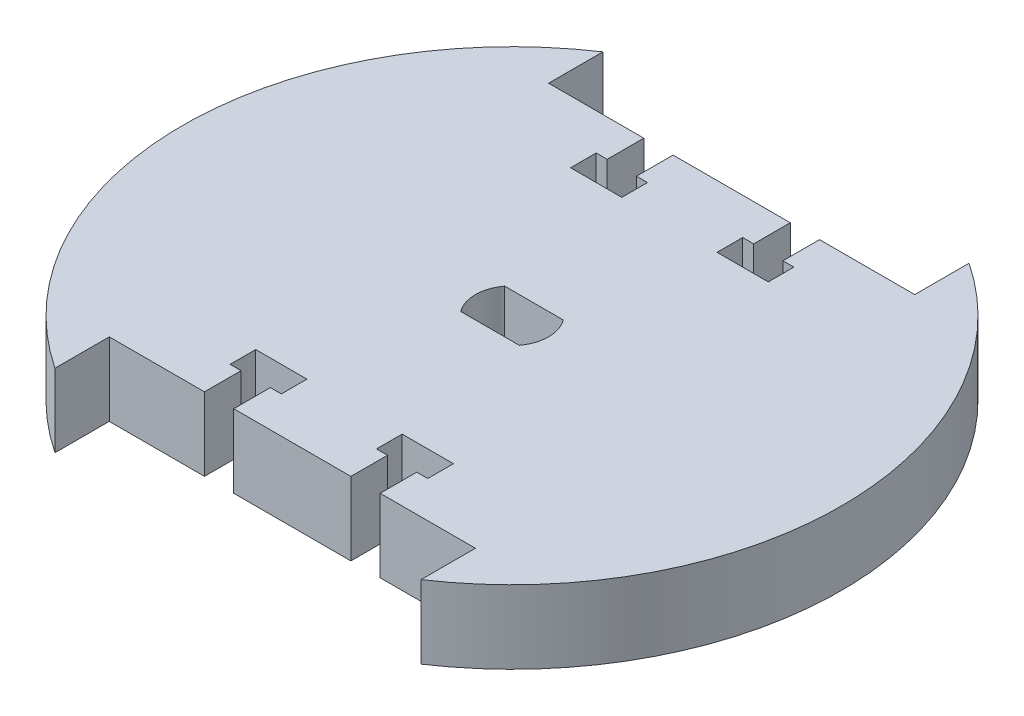
SolidWorks part; units mm, degrees
ref_plane "Piano frontale" through (0, 0, 0) normal (0, 0, 1) x (1, 0, 0)
ref_plane "Piano superiore" through (0, 0, 0) normal (0, 1, 0) x (1, 0, 0)
ref_plane "Piano destro" through (0, 0, 0) normal (1, 0, 0) x (0, 0, -1)
sketch "Schizzo1" plane through (0, 0, 0) normal (0, 1, 0) x (1, 0, 0)
  line L0 (-42.1632, 0) -> (43.9871, 0) construction
  line L1 (0, 30) -> (0, 0) construction
  line L2 (-25, 37.4166) -> (-25, 30)
  line L3 (-25, 30) -> (25, 30)
  line L4 (25, 37.4166) -> (25, 30)
  line L5 (0, 0) -> (0, -30) construction
  line L8 (-25, -37.4166) -> (-25, -30)
  line L9 (-25, -30) -> (25, -30)
  line L10 (25, -37.4166) -> (25, -30)
  arc A0 (-25, 37.4166) -> (-25, -37.4166) centre (0, 0) ccw
  arc A1 (25, -37.4166) -> (25, 37.4166) centre (0, 0) ccw
  point P3 (0, 45)
  point P8 (0, -45)
  dimension "D1" = 90
  dimension "D2" = 60
  dimension "D3" = 50
  dimension "D4" = 50
extrude "Estrusione-Estrusione1" add sketch "Schizzo1" along normal blind 10
sketch "Schizzo3" plane through (0, 10, 0) normal (0, 1, 0) x (1, 0, 0)
  line L0 (4, 3) -> (-4, 3)
  line L1 (-4, -3) -> (4, -3)
  line L2 (4, -3) -> (4, 3)
  line L3 (-4, 3) -> (-4, -3)
  circle A0 centre (0, 0) radius 5
  dimension "D1" = 10
  dimension "D2" = 6
extrude "Taglio-Estrusione2" cut sketch "Schizzo3" against normal through all contours L3 A0 | L0 L3 L1 L2 | L2 A0
sketch "Schizzo5" plane through (0, 10, 0) normal (0, 1, 0) x (1, 0, 0)
  line L1 (0, 0) -> (-13.5, 0)
  line L2 (-13.5, 25) -> (-12, 25)
  line L3 (-13.5, 21.5) -> (-13.5, 25)
  line L4 (-6.5, 25) -> (-6.5, 21.5)
  line L5 (13.5, 25) -> (13.5, 21.5)
  line L6 (6.5, 21.5) -> (13.5, 21.5)
  line L7 (-25, -30) -> (25, -30) construction
  line L8 (12, 30) -> (12, 27)
  line L9 (-8, 25) -> (-6.5, 25)
  line L10 (-13.5, 21.5) -> (-6.5, 21.5)
  line L11 (-8, 30) -> (-8, 28.5)
  line L12 (12, 25) -> (13.5, 25)
  line L13 (6.5, 25) -> (6.5, 21.5)
  line L14 (8, -28.5) -> (8, -30)
  line L15 (8, -28.5) -> (8, -25)
  line L16 (12, 27) -> (12, 25)
  line L17 (8, -30) -> (12, -30)
  line L18 (-8, 28.5) -> (-8, 25)
  line L19 (8, 25) -> (6.5, 25)
  line L20 (-12, -28.5) -> (-12, -30)
  line L21 (-12, -30) -> (-8, -30)
  line L22 (-12, -28.5) -> (-12, -25)
  line L23 (8, -25) -> (6.5, -25)
  line L24 (-8, -28.5) -> (-8, -25)
  line L25 (12, -27) -> (12, -25)
  line L26 (6.5, -25) -> (6.5, -21.5)
  line L27 (12, -25) -> (13.5, -25)
  line L28 (-8, -30) -> (-8, -28.5)
  line L29 (-13.5, -21.5) -> (-6.5, -21.5)
  line L30 (-8, -25) -> (-6.5, -25)
  line L31 (12, -30) -> (12, -27)
  line L32 (-12, 28.5) -> (-12, 25)
  line L33 (-12, 30) -> (-8, 30)
  line L34 (-12, 28.5) -> (-12, 30)
  line L35 (6.5, -21.5) -> (13.5, -21.5)
  line L36 (13.5, -25) -> (13.5, -21.5)
  line L37 (8, 30) -> (12, 30)
  line L38 (8, 28.5) -> (8, 25)
  line L39 (-6.5, -25) -> (-6.5, -21.5)
  line L40 (-13.5, -21.5) -> (-13.5, -25)
  line L41 (-13.5, -25) -> (-12, -25)
  line L42 (8, 28.5) -> (8, 30)
  line L43 (25, 37.4166) -> (25, 30) construction
  line L44 (4, 3) -> (-4, 3) construction
  point P12 (10, -30)
  point P19 (-10, -30)
  point P24 (-10, -25)
  point P33 (10, -25)
  point P53 (10, 25)
  point P54 (-10, 25)
  point P55 (-10, 30)
  point P56 (10, 30)
  line M11 (-25, -30) -> (25, -30)
  dimension "D3" = 15
  dimension "D4" = 15
  dimension "D11" = 4
  dimension "D12" = 4
  dimension "D13" = 7
  dimension "D16" = 7
extrude "Taglio-Estrusione3" cut sketch "Schizzo5" against normal through all contours L27 L36 L35 L26 L23 L15 L14 L31 L25 M11 | L10 L4 L9 L18 L11 L33 L34 L32 L2 L3 | L6 L5 L12 L16 L8 L37 L42 L38 L19 L13 | L24 L30 L39 L29 L40 L41 L22 L20 L21 L28
